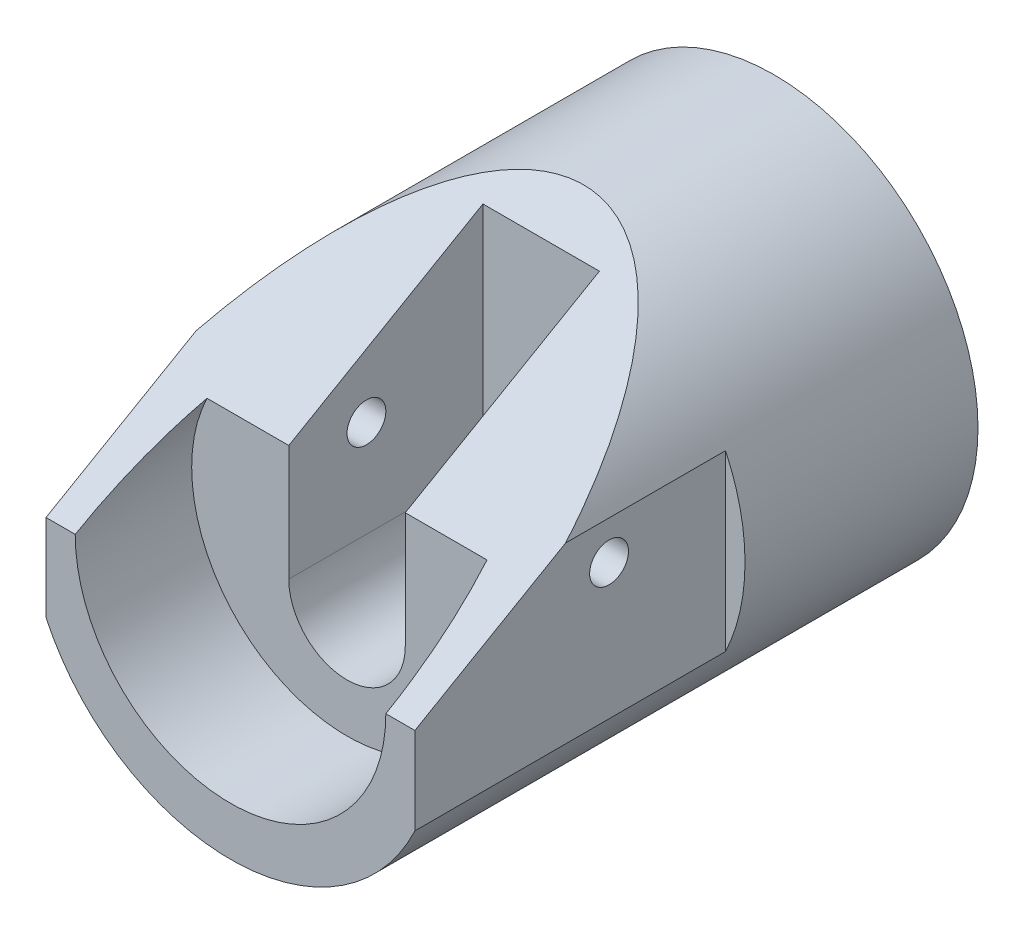
SolidWorks part; units mm, degrees
ref_plane "Alzado" through (0, 0, 0) normal (0, 0, 1) x (1, 0, 0)
ref_plane "Planta" through (0, 0, 0) normal (0, 1, 0) x (1, 0, 0)
ref_plane "Vista lateral" through (0, 0, 0) normal (1, 0, 0) x (0, 0, -1)
sketch "Croquis2" plane through (0, 0, 0) normal (0, 0, 1) x (1, 0, 0)
  line L1 (-33.3375, -33.3375) -> (33.3375, -33.3375)
  line L2 (-33.3375, -33.3375) -> (-33.3375, 33.3375)
  line L3 (-33.3375, 33.3375) -> (33.3375, 33.3375)
  line L4 (33.3375, -33.3375) -> (33.3375, 33.3375)
  line L5 (-33.3375, -33.3375) -> (33.3375, 33.3375) construction
  line L6 (-33.3375, 33.3375) -> (33.3375, -33.3375) construction
  point P0 (0, 0)
  dimension "D1" = 66.675
extrude "Saliente-Extruir2" add sketch "Croquis2" along normal blind 88.9
sketch "Croquis3" plane through (33.3375, 0, 0) normal (1, 0, 0) x (0, 0, -1)
  line L0 (-93.5569, 0) -> (8.4796, 0) construction
  line L1 (-88.9, 0) -> (-88.9, 33.3375)
  line L2 (-88.9, -33.3375) -> (-88.9, 33.3375) construction
  line L3 (-88.9, 33.3375) -> (-31.1578, 33.3375)
  line L4 (-88.9, 33.3375) -> (0, 33.3375) construction
  line L5 (-31.1578, 33.3375) -> (-88.9, 0)
  dimension "D1" = 30
extrude "Cortar-Extruir1" cut sketch "Croquis3" against normal through all
sketch "Croquis4" plane through (0, 0, 88.9) normal (0, 0, 1) x (1, 0, 0)
  circle A0 centre (0, 0) radius 25.4
  dimension "D1" = 50.8
extrude "Cortar-Extruir2" cut sketch "Croquis4" against normal blind 19.05
sketch "Croquis5" plane through (0, 0, 69.85) normal (0, 0, 1) x (1, 0, 0)
  line L0 (-9.525, -7.9248) -> (-9.525, 33.3375)
  line L1 (-33.3375, 33.3375) -> (33.3375, 33.3375) construction
  line L2 (-9.525, 33.3375) -> (9.525, 33.3375)
  line L3 (9.525, 33.3375) -> (9.525, -7.9248)
  arc A0 (-9.525, -7.9248) -> (9.525, -7.9248) centre (0, -7.9248) ccw
  dimension "D2" = 19.05
  dimension "D1" = 7.9248
extrude "Cortar-Extruir3" cut sketch "Croquis5" against normal blind 31.75
sketch "Croquis6" plane through (0, 0, 88.9) normal (0, 0, 1) x (1, 0, 0)
  circle A0 centre (0, 0) radius 33.3375
extrude "Cortar-Extruir5" cut sketch "Croquis6" against normal through all flip side to cut
sketch "Croquis8" plane through (0, 0, 88.9) normal (0, 0, 1) x (1, 0, 0)
  line L0 (-30.1752, 14.172) -> (-30.1752, -14.172)
  line L1 (30.1498, 14.226) -> (30.1498, -14.226)
  arc A0 (-30.1752, 14.172) -> (-30.1752, -14.172) centre (0, 0) ccw
  arc A1 (30.1498, -14.226) -> (30.1498, 14.226) centre (0, 0) ccw
  dimension "D1" = 30.1752
  dimension "D2" = 60.325
extrude "Cortar-Extruir6" cut sketch "Croquis8" against normal blind 50.8
sketch "Croquis9" plane through (30.1498, 0, 0) normal (1, 0, 0) x (0, 0, -1)
  line L0 (0, 0) -> (-88.9, 0) construction
  circle A0 centre (-57.15, 7.9248) radius 3.175
  dimension "D1" = 6.35
  dimension "D2" = 7.9248
  dimension "D3" = 31.75
extrude "Cortar-Extruir7" cut sketch "Croquis9" against normal blind 60.325
